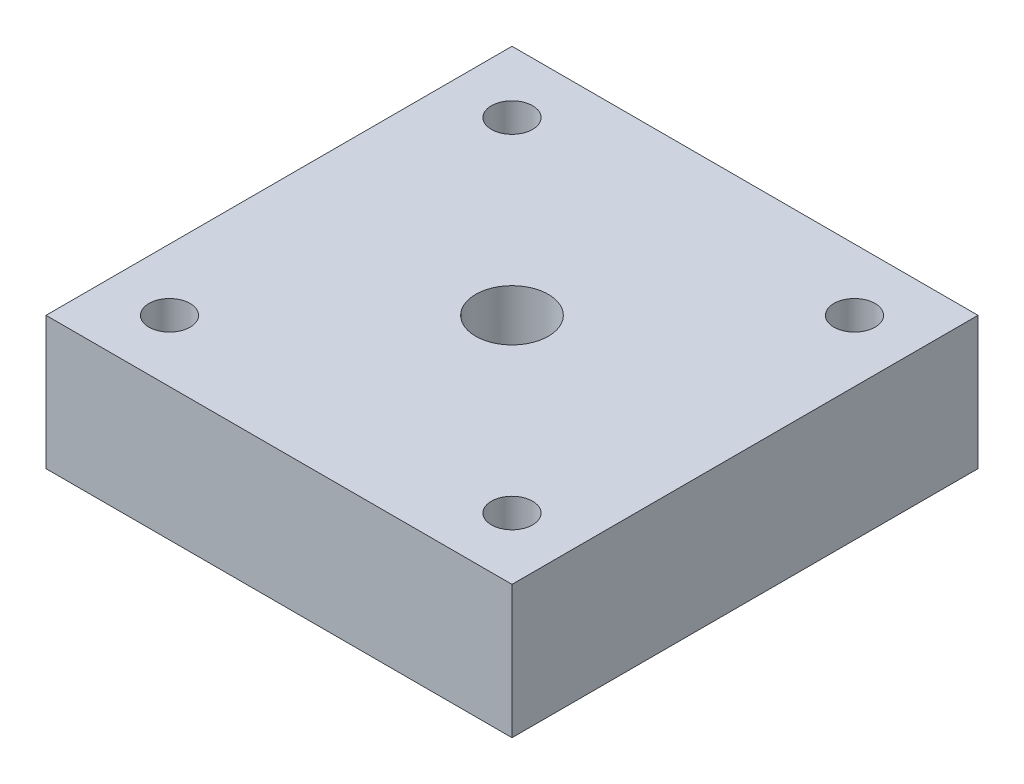
SolidWorks part; units mm, degrees
material "1060 Alloy"
ref_plane "Front" through (0, 0, 0) normal (0, 0, 1) x (1, 0, 0)
ref_plane "Top" through (0, 0, 0) normal (0, 1, 0) x (1, 0, 0)
ref_plane "Right" through (0, 0, 0) normal (1, 0, 0) x (0, 0, -1)
sketch "Sketch1" plane through (0, 0, 0) normal (0, 1, 0) x (1, 0, 0)
  line L1 (-48.1053, 48.1053) -> (48.1053, 48.1053)
  line L2 (-48.1053, 48.1053) -> (-48.1053, -48.1053)
  line L3 (-48.1053, -48.1053) -> (48.1053, -48.1053)
  line L4 (48.1053, 48.1053) -> (48.1053, -48.1053)
  line L5 (-48.1053, 48.1053) -> (48.1053, -48.1053) construction
  line L6 (-48.1053, -48.1053) -> (48.1053, 48.1053) construction
  circle A0 centre (-35.3553, 35.3553) radius 4.25
  circle A1 centre (35.3553, 35.3553) radius 4.25
  circle A2 centre (35.3553, -35.3553) radius 4.25
  circle A3 centre (-35.3553, -35.3553) radius 4.25
  point P0 (0, 0)
  point P17 (0, 0)
  dimension "D3" = 8.5
  dimension "D2" = 50
  dimension "D5" = 50
  dimension "D6" = 50
  dimension "D1" = 12.75
  dimension "D7" = 96.2107
  dimension "D4" = 4
extrude "body extrusion and bolt holes" add sketch "Sketch1" along normal blind 27.4255
sketch "Sketch2" plane through (0, 0, 0) normal (0, 0, 1) x (1, 0, 0)
  line L0 (0, 0) -> (0, 19.4255)
  line L1 (-48.1053, 0) -> (48.1053, 0) construction
  line L2 (0, 19.4255) -> (22.725, 9.85)
  line L3 (22.725, 9.85) -> (22.725, 0)
  line L4 (22.725, 0) -> (0, 0)
  dimension "D1" = 22.725
  dimension "D2" = 19.4255
  dimension "D3" = 9.85
revolve "main chamber" cut sketch "Sketch2" angle 360 about L0
sketch "Sketch3" plane through (0, 27.4255, 0) normal (0, 1, 0) x (1, 0, 0)
  circle A0 centre (0, 0) radius 7.5
  dimension "D1" = 15
extrude "entrance" cut sketch "Sketch3" against normal blind 27.4255
sketch "Sketch5" plane through (0, 0, 0) normal (1, 0, 0) x (0, 0, -1)
  line L0 (-22.725, 9.85) -> (22.725, 9.85) construction
  line L1 (-22.725, 9.85) -> (-22.725, 0) construction
  circle A0 centre (-19.55, 6.675) radius 3.175
  dimension "D1" = 6.35
extrude "outlet" cut sketch "Sketch5" against normal blind 100
equation "\"motor mount pattern diameter\"= 30mm"
equation "\"D2@Sketch1\" = \"motor mount to housing m8 pattern diameter\" / 2"
equation "\"D3@Sketch1\" = \"motor mount to housing m8 screw hole diameter\""
equation "\"D5@Sketch1\" = \"motor mount to housing m8 pattern diameter\" / 2"
equation "\"D6@Sketch1\" = \"motor mount to housing m8 pattern diameter\" / 2"
equation "\"D1@Sketch1\" = \"motor mount to housing m8 screw post radius\""
equation "\"D1@body extrusion and bolt holes\" = \"housing top total thickness\""
equation "\"D1@Sketch2\" = \"housing top impeller cavity diameter\" / 2"
equation "\"D2@Sketch2\" = \"housing top impeller cavity height\""
equation "\"D3@Sketch2\" = \"housing top impeller cavity tip height\""
equation "\"D1@Sketch3\"=\"de\""
equation "\"D1@entrance\" = \"housing top total thickness\""
equation "\"bearing OD\" = 20mm"
equation "\"bearing outer race thickness\"= 1mm"
equation "\"bearing ID\"= 10mm"
equation "\"bearing depth\"= 6mm"
equation "\"bearing inner race thickness\"= 1mm"
equation "\"seal OD\" = 20mm"
equation "\"seal ID\"= 8mm"
equation "\"seal depth\"= 6mm"
equation "\"impeller base outer diameter\"= \"d2\""
equation "\"impeller base outer thickness\"= 2mm"
equation "\"impeller base center thickness\"= \"impeller base outer thickness\""
equation "\"impeller number of vanes\"= \"z\""
equation "\"impeller vane inner height\"= \"b1\""
equation "\"impeller primary vane opening diamater\"= \"de\""
equation "\"impeller vane inner thickness\"= \"s\""
equation "\"impeller vane outer thickness\"= \"s\""
equation "\"impeller primary vane entrance angle\"= 0deg"
equation "\"impeller secondary vane entrance angle\"= 0deg"
equation "\"impeller secondary vane opening diameter\"= \"de\""
equation "\"motor to housing distance\"= 60mm"
equation "\"motor mount coupler shaft hole diameter\"= \"coupler shaft base diameter\"+ 4mm"
equation "\"motor mount to housing m8 screw hole diameter\"= 8.5mm"
equation "\"motor mount to housing m8 screw post radius\"= ( 3 * \"motor mount to housing m8 screw hole diameter\" ) / 2"
equation "\"motor mount to housing m8 pattern diameter\"= 100mm"
equation "\"motor mount to housing m4 screw hole diamater\"= 4mm"
equation "\"motor mount to housing m4 head diameter\"= 7.25mm"
equation "\"motor mount to housing m4 head depth\"= 4mm"
equation "\"motor mount plate thickness\"= 6mm + \"motor mount to housing m4 head depth\""
equation "\"housing bearing seat lip thickness\" = 2mm"
equation "\"housing base thickness\"= \"housing bearing seat lip thickness\" + \"seal depth\" + \"bearing depth\""
equation "\"housing top impeller vertical clearance\"= .5mm"
equation "\"housing top impeller horizontal clearance\"= .5mm"
equation "\"housing top impeller bottom clearance\"= 1mm"
equation "\"housing top impeller cavity height\"= \"housing top impeller bottom clearance\" + \"impeller base center thickness\" + \"impeller vane inner height\" + \"housing top impeller vertical clearance\""
equation "\"housing top impeller cavity diameter\"= 2 * \"housing top impeller horizontal clearance\" + \"impeller base outer diameter\""
equation "\"housing top impeller cavity tip height\"= \"housing top impeller bottom clearance\" + \"housing top impeller vertical clearance\" + \"impeller base outer thickness\" + \"impeller vane outer height\""
equation "\"housing top entrance OD\"= 20mm"
equation "\"housing top exit OD\"= \"d_exit\""
equation "\"housing top o-ring channel height\"= 1.5mm"
equation "\"housing top o ring channel width\"= 1.5mm"
equation "\"housing top threaded inlet depth\"= 8mm"
equation "\"housing top total thickness\"= \"housing top threaded inlet depth\" + \"housing top impeller cavity height\""
equation "\"housing top total width\"= 10mm"
equation "\"housing top exit threaded diameter\"= 8mm"
equation "\"housing top exit threaded depth\"= 8mm"
equation "\"motor shaft pride\"= 32mm"
equation "\"motor shaft flat section length from tip\"= 25.7mm"
equation "\"motor shaft bore end clearance\"= 2mm"
equation "\"motor mount shaft hole depth\"= \"motor shaft pride\""
equation "\"coupler shaft set screw drill hole diameter\"= 6mm"
equation "\"coupler shaft set screw 1 distance\"= \"motor mount shaft hole depth\" / 3"
equation "\"coupler shaft set screw 2 distance\"= \"motor mount shaft hole depth\" * 4 / 5"
equation "\"coupler shaft motor shaft hole diameter\"= 8mm"
equation "\"coupler shaft base diameter\"= 18mm"
equation "\"coupler shaft base length\"= \"motor mount shaft hole depth\" + 10mm"
equation "\"coupler shaft second section diameter\"= \"bearing ID\" + \"bearing inner race thickness\" * 2"
equation "\"coupler shaft second section length\"= \"motor to housing distance\" -  \"coupler shaft base length\" - 2mm"
equation "\"coupler shaft third section diamater\"= \"bearing ID\""
equation "\"coupler shaft third section length\"= \"bearing depth\""
equation "\"coupler shaft seal section diameter\" = \"seal ID\""
equation "\"coupler shaft seal section length\" = \"housing base thickness\"+\"housing top impeller bottom clearance\"-\"bearing depth\""
equation "\"coupler shaft impeller section diameter\" = 6mm"
equation "\"coupler shaft impeller section length\" = \"impeller boss depth\"+\"impeller base center thickness\" - 1mm"
equation "\"coupler shaft impeller screw hole diameter\" = \"motor mount to housing m4 screw hole diamater\""
equation "\"coupler shaft impeller screw hole depth\" = 10mm"
equation "\"housing top o-ring circumference\" = 250mm"
equation "\"housing top o-ring radius\" = (\"housing top o-ring circumference\")/(2*3.14)"
equation "\"impeller vane outer height\"= \"b2\""
equation "\"impeller bolt surface height\" = 5mm"
equation "\"impeller bolt surface diameter\" = 8mm"
equation "\"impeller boss depth\" = 5mm"
equation "\"impeller dowel diameter\" = 2mm"
equation "\"coupler shaft to motor clearance\" = 2mm"
equation "\"impeller boss diameter\" = \"coupler shaft impeller section diameter\"+2*5mm"
equation "\"impeller dowel length\" = 2mm*2 + \"coupler shaft impeller section diameter\""
equation "\"D1@Sketch5\"=\"housing top exit OD\" "
equation "\"z\" = 10"
equation "\"de\" = 15mm"
equation "\"d2\" = 1.75in"
equation "\"theta\" = 15"
equation "\"b2\" = \"d_exit\""
equation "\"b1\" = \"b2\" + (\"d2\"/2 - \"de\"/2)*sin(\"theta\")"
equation "\"s\" = ( 1/\"z\")*(3.14*\"de\" - (3.14*(\"de\"^2) / (4*(\"b1\"))))"
equation "\"s_opening\" = (3.14*\"de\" - \"z\"*\"s\")/\"z\""
equation "\"d_exit\" = .25in"
